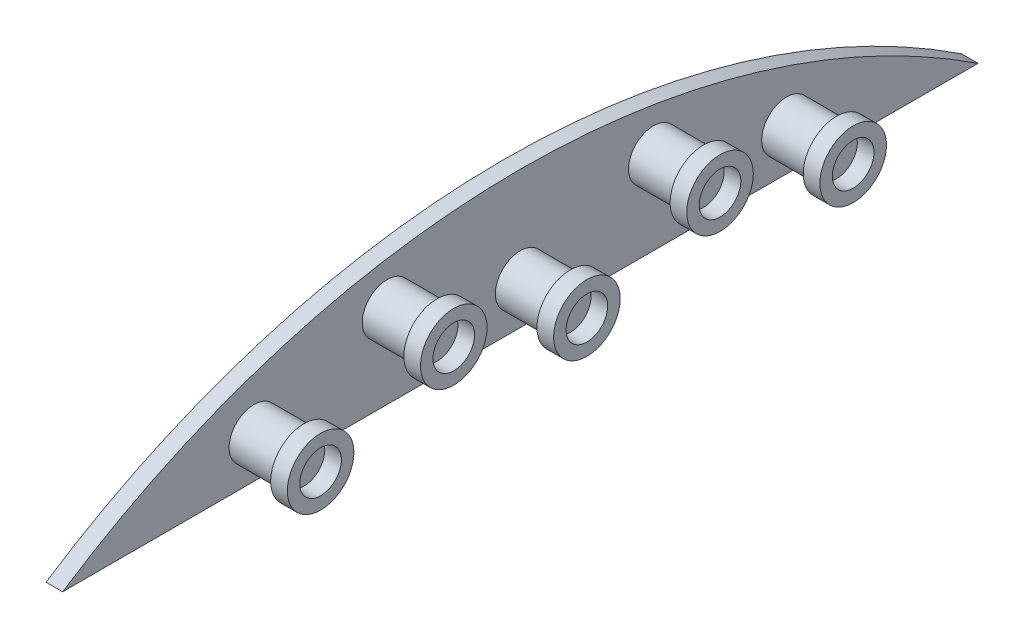
SolidWorks part; units mm, degrees
ref_plane "正面" through (0, 0, 0) normal (0, 0, 1) x (1, 0, 0)
ref_plane "平面" through (0, 0, 0) normal (0, 1, 0) x (1, 0, 0)
ref_plane "右側面" through (0, 0, 0) normal (1, 0, 0) x (0, 0, -1)
sketch "ｽｹｯﾁ1" plane through (0, 0, 0) normal (1, 0, 0) x (0, 0, -1)
  line L0 (0, 0) -> (110, 0)
  line L1 (55, 32.5283) -> (55, -121.8911) construction
  arc A0 (110, 0) -> (0, 0) centre (55, -83.5165) ccw
  dimension "D3" = 100
  dimension "D1" = 110
  dimension "D2" = 55
extrude "押し出し1" add sketch "ｽｹｯﾁ1" along normal blind 2 contours L1 A0 L0 | A0 L1 L0
sketch "ｽｹｯﾁ2" plane through (2, 0, 0) normal (1, 0, 0) x (0, 0, -1)
  line L0 (2.9109, 5) -> (102.6633, 5) construction
  line L1 (0, 0) -> (110, 0) construction
  line L2 (5.4643, 10) -> (95.0031, 10) construction
  line L3 (55, 13.7741) -> (55, 2) construction
  line L4 (39, 13.7741) -> (39, 2.0285) construction
  line L5 (23, 12.4123) -> (23, 2) construction
  line L6 (71, 13.7741) -> (71, 2.0285) construction
  line L7 (87, 13.7741) -> (87, 2) construction
  arc A0 (110, 0) -> (0, 0) centre (55, -83.5165) ccw construction
  circle A1 centre (23, 5) radius 3
  circle A2 centre (39, 10) radius 3
  circle A3 centre (55, 5) radius 3
  circle A4 centre (71, 10) radius 3
  circle A5 centre (87, 5) radius 3
  point P4 (55, 16.4835)
  point P8 (55, 0)
  dimension "D9" = 6
  dimension "D10" = 6
  dimension "D11" = 6
  dimension "D12" = 6
  dimension "D13" = 6
  dimension "D1" = 5
  dimension "D2" = 16.4835
  dimension "D3" = 5
  dimension "D4" = 55
  dimension "D5" = 16
  dimension "D6" = 16
  dimension "D7" = 16
  dimension "D8" = 16
extrude "押し出し2" add sketch "ｽｹｯﾁ2" along normal blind 6
sketch "ｽｹｯﾁ3" plane through (8, 0, 0) normal (1, 0, 0) x (0, 0, -1)
  circle A0 centre (23, 5) radius 4
  circle A1 centre (39, 10) radius 4
  circle A2 centre (55, 5) radius 4
  circle A3 centre (71, 10) radius 4
  circle A4 centre (87, 5) radius 4
  circle A5 centre (23, 5) radius 2.5
  circle A6 centre (39, 10) radius 4
  circle A7 centre (55, 5) radius 4
  circle A8 centre (71, 10) radius 4
  circle A9 centre (87, 5) radius 4
  circle A13 centre (39, 10) radius 2.5
  circle A14 centre (55, 5) radius 2.5
  circle A15 centre (71, 10) radius 2.5
  circle A16 centre (87, 5) radius 2.5
  dimension "D1" = 8
  dimension "D2" = 8
  dimension "D3" = 8
  dimension "D4" = 8
  dimension "D5" = 8
  dimension "D6" = 5
  dimension "D7" = 5
  dimension "D8" = 5
  dimension "D9" = 5
  dimension "D10" = 5
extrude "押し出し3" add sketch "ｽｹｯﾁ3" along normal blind 2 contours A0 | A5 | A1 | A13 | A2 | A14 | A3 | A15 | A4 | A16
